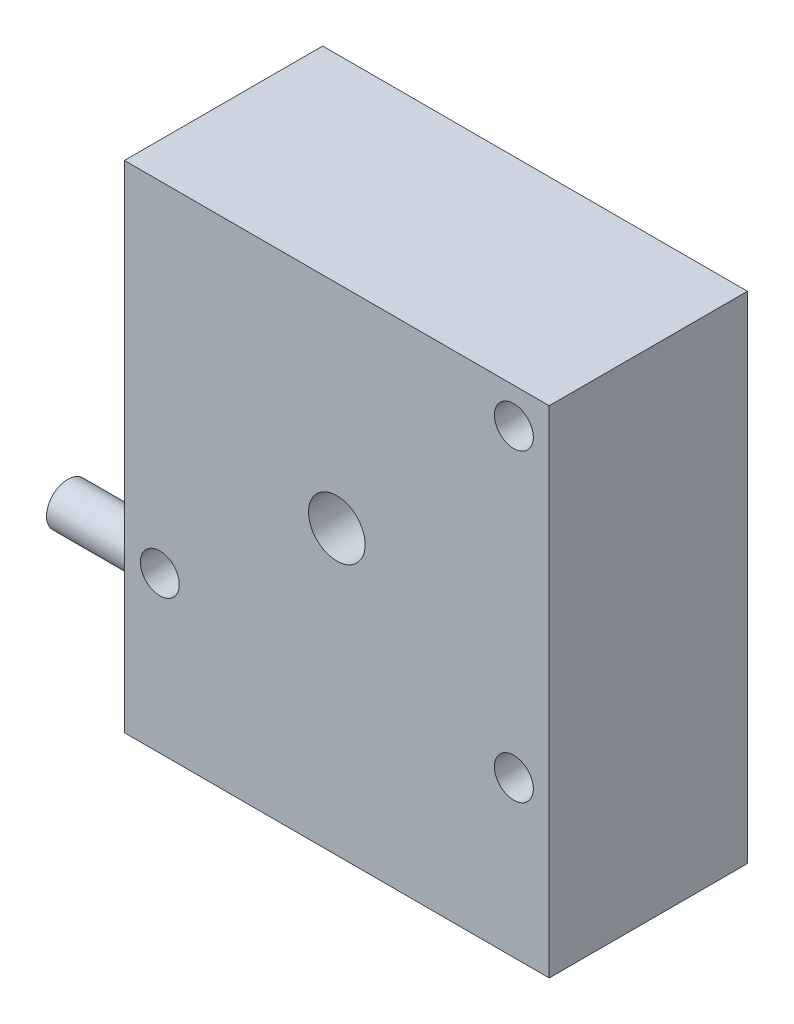
SolidWorks part; units mm, degrees
ref_plane "Plan de face" through (0, 0, 0) normal (0, 0, 1) x (1, 0, 0)
ref_plane "Plan de dessus" through (0, 0, 0) normal (0, 1, 0) x (1, 0, 0)
ref_plane "Plan de droite" through (0, 0, 0) normal (1, 0, 0) x (0, 0, -1)
sketch "Esquisse1" plane through (0, 0, 0) normal (0, 0, 1) x (1, 0, 0)
  line L1 (0, 0) -> (60, 0)
  line L2 (0, 0) -> (0, 70)
  line L3 (0, 70) -> (60, 70)
  line L4 (60, 0) -> (60, 70)
  dimension "D1" = 70
  dimension "D2" = 60
extrude "Extrusion1" add sketch "Esquisse1" against normal blind 28
sketch "Esquisse2" plane through (0, 0, 0) normal (-1, 0, 0) x (0, 0, 1)
  line L1 (-28, 70) -> (-28, 0) construction
  line L2 (-28, 0) -> (0, 0) construction
  circle A0 centre (-14, 10) radius 3
  dimension "D3" = 6
  dimension "D1" = 10
  dimension "D2" = 14
extrude "Extrusion2" add sketch "Esquisse2" along normal blind 22
sketch "Esquisse3" plane through (0, 0, 0) normal (0, 0, 1) x (1, 0, 0)
  line L0 (60, 0) -> (60, 70) construction
  line L2 (60, 70) -> (0, 70) construction
  circle A0 centre (30, 40) radius 4
  dimension "D1" = 8
  dimension "D2" = 30
  dimension "D3" = 30
extrude "Extrusion3" cut sketch "Esquisse3" against normal up to next
hole_wizard "Dégagement M51" positions "Esquisse3D4" profile "Esquisse8" hole size "M5" standard "ISO" end condition through all
sketch3d "Esquisse3D4"
  line L0 (60, 0, -28) -> (60, 70, -28) construction
  line L1 (60, 70, -28) -> (0, 70, -28) construction
  line L3 (0, 70, -28) -> (0, 0, -28) construction
  point P0 (55, 22, -28)
  point P2 (55, 65, -28)
  point P13 (5, 22, -28)
  dimension "D1" = 5
  dimension "D2" = 5
  dimension "D3" = 5
  dimension "D4" = 50
  dimension "D5" = 5
  dimension "D6" = 43
sketch "Esquisse8" plane through (55, 22, -28) normal (1, 0, 0) x (0, 1, 0)
  line L0 (0, 0) -> (0, 28)
  line L1 (0, 28) -> (2.75, 28)
  line L2 (2.75, 28) -> (2.75, 0)
  line L5 (2.75, 0) -> (0, 0)
  line L11 (0, -6.35) -> (0, 107.95) construction
  dimension "Diamètre du perçage jusqu'au prochain" = 5.5
  dimension "Profondeur du perçage jusqu'au prochain" = 28
